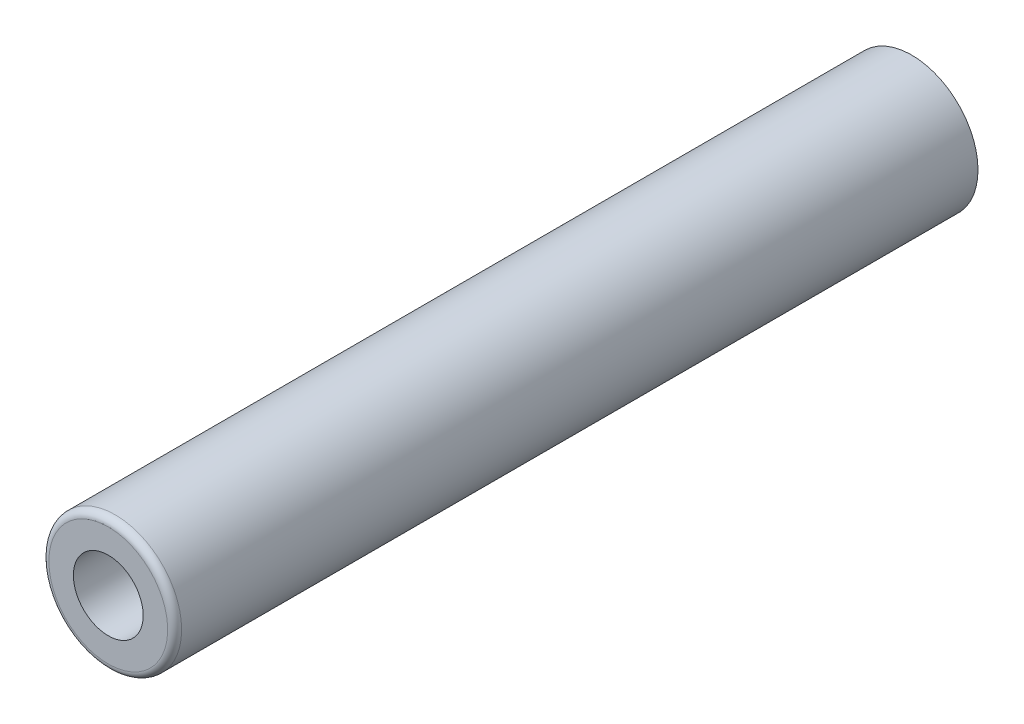
SolidWorks part; units mm, degrees
material "AISI 4130 Steel, normalized at 870C"
ref_plane "Front Plane" through (0, 0, 0) normal (1, 0, 0) x (0, 1, 0)
ref_plane "Top Plane" through (0, 0, 0) normal (0, 0, 1) x (0, 1, 0)
ref_plane "Right Plane" through (0, 0, 0) normal (0, 1, 0) x (-1, 0, 0)
sketch "Sketch1" plane through (0, 0, 0) normal (1, 0, 0) x (0, 1, 0)
  line L0 (0, 319.3174) -> (0, -301.3254) construction
  line L1 (-332.8603, 0) -> (362.1851, 0) construction
  line L2 (10, 115) -> (19, 115)
  line L3 (19, 115) -> (19, -115)
  line L4 (19, -115) -> (15, -115)
  line L5 (10, 75) -> (15, 75)
  line L6 (10, 115) -> (10, 75)
  line L7 (15, 75) -> (15, -115)
  point P13 (19, 0)
  dimension "D1" = 40
  dimension "D2" = 230
  dimension "D3" = 20
  dimension "D4" = 38
  dimension "D5" = 4
revolve "Revolve1" add sketch "Sketch1" angle 360 about L0
fillet "Fillet1" radius 2 1 edges at (19, 0, 115)
